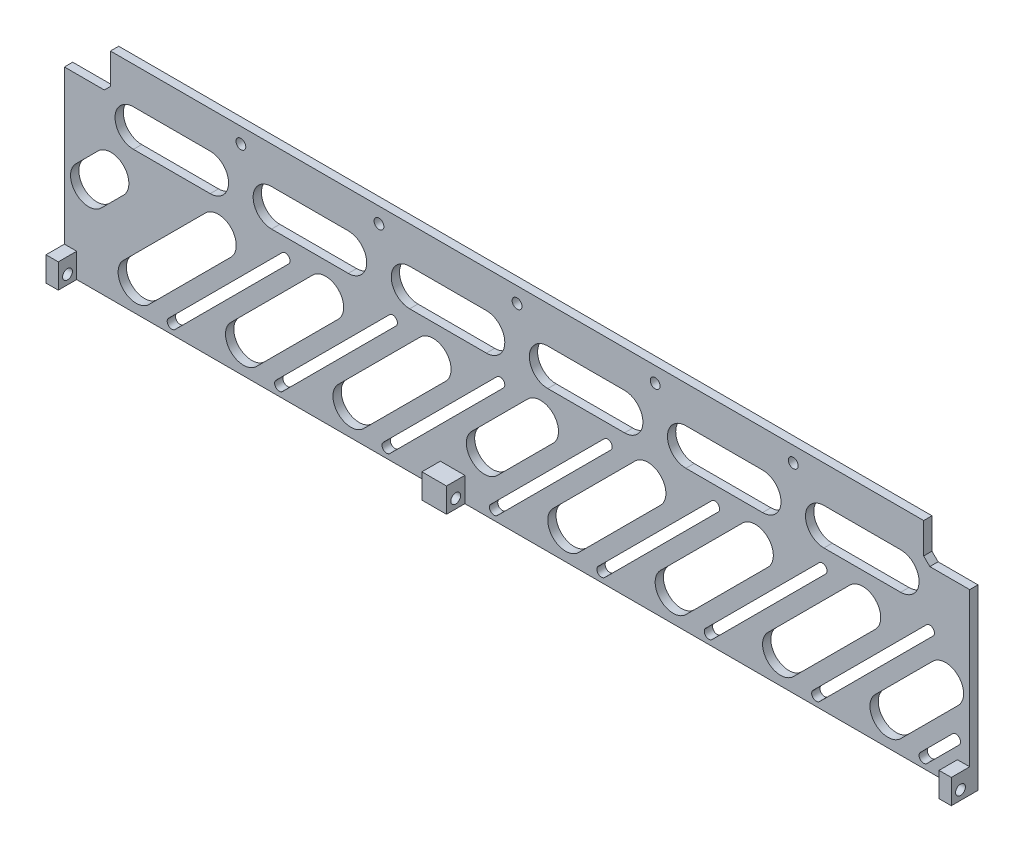
SolidWorks part; units mm, degrees
ref_plane "前视基准面" through (0, 0, 0) normal (0, 0, 1) x (1, 0, 0)
ref_plane "上视基准面" through (0, 0, 0) normal (0, 1, 0) x (1, 0, 0)
ref_plane "右视基准面" through (0, 0, 0) normal (1, 0, 0) x (0, 0, -1)
sketch "草图1" plane through (0, 0, 0) normal (0, 0, 1) x (1, 0, 0)
  line L1 (-147.5, 35) -> (147.5, 35)
  line L2 (-147.5, 35) -> (-147.5, -35)
  line L3 (-147.5, -35) -> (147.5, -35)
  line L4 (147.5, 35) -> (147.5, -35)
  line L5 (-147.5, 35) -> (147.5, -35) construction
  line L6 (-147.5, -35) -> (147.5, 35) construction
  point P0 (0, 0)
  dimension "D1" = 295
  dimension "D2" = 70
extrude "凸台-拉伸1" add sketch "草图1" along normal blind 2.7
sketch "草图11" plane through (0, 0, 2.7) normal (0, 0, 1) x (1, 0, 0)
  line L0 (-147.5, 35) -> (-147.5, 23)
  line L1 (-147.5, 35) -> (-147.5, -35) construction
  line L2 (-147.5, 23) -> (-134.5, 23)
  line L3 (-134.5, 23) -> (-132.5, 25)
  line L4 (-132.5, 25) -> (-132.5, 35)
  line L5 (147.5, 35) -> (-147.5, 35) construction
  line L6 (-132.5, 35) -> (-147.5, 35)
  line L13 (0, 35) -> (0, -35) construction
  line L14 (-147.5, -35) -> (147.5, -35) construction
  line L15 (132.5, 35) -> (147.5, 35)
  line L16 (132.5, 25) -> (132.5, 35)
  line L17 (134.5, 23) -> (132.5, 25)
  line L18 (147.5, 23) -> (134.5, 23)
  line L19 (147.5, 35) -> (147.5, 23)
  dimension "D1" = 15
  dimension "D2" = 12
  dimension "D3" = 135
  dimension "D4" = 10
extrude "切除-拉伸5" cut sketch "草图11" against normal blind 10
sketch "草图2" plane through (0, 0, 2.7) normal (0, 0, 1) x (1, 0, 0)
  line L1 (0, -32) -> (0, 35) construction
  line L2 (132.5, 35) -> (-132.5, 35) construction
  line L3 (-147.5, 23) -> (-147.5, -35) construction
  line L4 (-112.5, -32) -> (-75.5, 5) construction
  line L5 (-113.5607, -30.9393) -> (-76.5607, 6.0607)
  line L6 (-111.4393, -33.0607) -> (-74.4393, 3.9393)
  line L7 (-147.5, -35) -> (147.5, -35) construction
  arc A1 (-113.5607, -30.9393) -> (-111.4393, -33.0607) centre (-112.5, -32) ccw
  arc A2 (-74.4393, 3.9393) -> (-76.5607, 6.0607) centre (-75.5, 5) ccw
  point P4 (-94, -13.5)
  dimension "D2" = 3
  dimension "D3" = 45
  dimension "D4" = 3
  dimension "D5" = 40
  dimension "D10" = 35
extrude "切除-拉伸1" cut sketch "草图2" against normal through all
pattern_linear "阵列(线性)1" count 7 spacing 35 along (1, 0, 0) of "切除-拉伸1"
sketch "草图10" plane through (0, 0, 2.7) normal (0, 0, 1) x (1, 0, 0)
  line L0 (132.5, -32) -> (143, -21.5) construction
  line L3 (131.4393, -30.9393) -> (141.9393, -20.4393)
  line L9 (133.5607, -33.0607) -> (144.0607, -22.5607)
  line L13 (62.5, -32) -> (132.5, -32) construction
  line L14 (147.5, -35) -> (147.5, 23) construction
  line L15 (63.5607, -33.0607) -> (100.5607, 3.9393) construction
  line L16 (144.5, -8.0249) -> (144.5, -29.8766) construction
  arc A4 (131.4393, -30.9393) -> (133.5607, -33.0607) centre (132.5, -32) ccw
  arc A5 (144.0607, -22.5607) -> (141.9393, -20.4393) centre (143, -21.5) ccw
  point P2 (137.75, -26.75)
  dimension "D1" = 15
  dimension "D2" = 70
  dimension "D3" = 3
  dimension "D4" = 3
extrude "切除-拉伸4" cut sketch "草图10" against normal through all
sketch "草图5" plane through (0, 0, 2.7) normal (0, 0, 1) x (1, 0, 0)
  line L0 (-147.5, -35) -> (147.5, -35) construction
  line L1 (-147.5, -35) -> (-143.5, -35)
  line L2 (-147.5, -35) -> (-147.5, -27)
  line L3 (-147.5, -27) -> (-143.5, -27)
  line L4 (-143.5, -35) -> (-143.5, -27)
  line L5 (147.5, -35) -> (143.5, -35)
  line L6 (147.5, -35) -> (147.5, -27)
  line L7 (147.5, -27) -> (143.5, -27)
  line L8 (143.5, -35) -> (143.5, -27)
  line L9 (-25, -35) -> (-17, -35)
  line L10 (-25, -35) -> (-25, -27)
  line L11 (-25, -27) -> (-17, -27)
  line L12 (-17, -35) -> (-17, -27)
  line L13 (-21, -32) -> (-7.5, -32) construction
  line L14 (-21, -32) -> (-21, -27) construction
  dimension "D1" = 8
  dimension "D2" = 8
  dimension "4" = 4
  dimension "D3" = 13.5
extrude "凸台-拉伸3" add sketch "草图5" along normal blind 6
sketch "草图7" plane through (-143.5, 0, 0) normal (1, 0, 0) x (0, 0, -1)
  line L0 (-8.7, -35) -> (-2.7, -35) construction
  line L1 (-5.7, -32) -> (-5.7, -35) construction
  circle A0 centre (-5.7, -32) radius 1.6
  dimension "D2" = 3.2
  dimension "D1" = 3
extrude "切除-拉伸3" cut sketch "草图7" against normal through all both and the other way through all
sketch "草图12" plane through (0, 0, 2.7) normal (0, 0, 1) x (1, 0, 0)
  line L0 (-89.1256, -26.1256) -> (-62.3744, 0.6256) construction
  line L1 (-93.2794, -21.9718) -> (-66.5282, 4.7794)
  line L2 (-84.9718, -30.2794) -> (-58.2206, -3.5282)
  line L3 (-76.5607, 6.0607) -> (-113.5607, -30.9393) construction
  line L4 (-111.4393, -33.0607) -> (-74.4393, 3.9393) construction
  line L5 (-41.5607, 6.0607) -> (-78.5607, -30.9393) construction
  line L6 (-143.5, -35) -> (-25, -35) construction
  line L7 (-88.1053, 6.5) -> (-19.4368, 6.5) construction
  line L8 (-59.1196, -32) -> (-128.8233, -32) construction
  arc A0 (-93.2794, -21.9718) -> (-84.9718, -30.2794) centre (-89.1256, -26.1256) ccw
  arc A1 (-58.2206, -3.5282) -> (-66.5282, 4.7794) centre (-62.3744, 0.6256) ccw
  arc A3 (-74.4393, 3.9393) -> (-76.5607, 6.0607) centre (-75.5, 5) ccw construction
  point P2 (-75.75, -12.75)
  dimension "D3" = 3
  dimension "D1" = 5
  dimension "D2" = 5
extrude "切除-拉伸6" cut sketch "草图12" against normal through all
pattern_linear "阵列(线性)2" count 7 spacing 35 along (1, 0, 0) of "切除-拉伸6"
pattern_linear "阵列(线性)3" count 3 spacing 35 along (-1, 0, 0) of "切除-拉伸6"
sketch "草图13" plane through (0, 0, 2.7) normal (0, 0, 1) x (1, 0, 0)
  line L0 (-35, 17) -> (-10, 17) construction
  line L1 (-35, 23) -> (-10, 23)
  line L2 (-35, 11) -> (-10, 11)
  line L3 (132.5, 35) -> (-132.5, 35) construction
  line L5 (0, 35) -> (0, -79.5814) construction
  arc A0 (-35, 23) -> (-35, 11) centre (-35, 17) ccw
  arc A1 (-10, 11) -> (-10, 23) centre (-10, 17) ccw
  point P2 (-22.5, 17)
  dimension "D1" = 18
  dimension "D2" = 25
  dimension "D3" = 12
  dimension "D4" = 22.5
extrude "切除-拉伸7" cut sketch "草图13" against normal through all
pattern_linear "阵列(线性)4" count 4 spacing 45 along (1, 0, 0) of "切除-拉伸7"
pattern_linear "阵列(线性)5" count 3 spacing 45 along (-1, 0, 0) of "切除-拉伸7"
sketch "草图14" plane through (0, 0, 2.7) normal (0, 0, 1) x (1, 0, 0)
  line L0 (-136.5282, 4.7794) -> (-147.5, -6.1924) construction
  line L3 (3.4718, 4.7794) -> (-23.2794, -21.9718) construction
  line L6 (143.4718, 4.7794) -> (116.7206, -21.9718) construction
  line L7 (145.5, 14.2028) -> (145.5, -16.5331) construction
  line L8 (147.5, -27) -> (147.5, -7.8076) construction
  line L9 (-145.5, 6.8282) -> (-145.5, -26.8886) construction
  line L10 (-147.5, 23) -> (-147.5, -6.1924) construction
  line L11 (-14.9718, -30.2794) -> (11.7794, -3.5282) construction
  line L12 (-143.7794, -2.4718) -> (-147.5, -6.1924)
  line L13 (-147.5, -6.1924) -> (-147.5, -22.8076)
  line L14 (-147.5, -22.8076) -> (-135.4718, -10.7794)
  line L15 (143.4718, 4.7794) -> (135.4718, -3.2206)
  line L16 (125.0282, -30.2794) -> (147.5, -7.8076) construction
  line L17 (143.7794, -11.5282) -> (147.5, -7.8076)
  line L18 (147.5, 6.4987) -> (147.5, -7.8076)
  line L21 (-14.7942, -13.4865) -> (-23.2794, -21.9718)
  line L25 (-10.6403, -17.6403) -> (-19.1256, -26.1256) construction
  line L26 (-6.4865, -21.7942) -> (-14.9718, -30.2794)
  arc A1 (-143.7794, -2.4718) -> (-135.4718, -10.7794) centre (-139.6256, -6.6256) ccw
  arc A3 (143.7794, -11.5282) -> (135.4718, -3.2206) centre (139.6256, -7.3744) ccw
  arc A4 (147.5, 6.4987) -> (143.4718, 4.7794) centre (147.6256, 0.6256) ccw construction
  arc A5 (147.5, 6.4987) -> (143.4718, 4.7794) centre (147.6256, 0.6256) ccw
  arc A7 (-23.2794, -21.9718) -> (-14.9718, -30.2794) centre (-19.1256, -26.1256) ccw
  arc A8 (-23.2794, -21.9718) -> (-24.9346, -27) centre (-19.1256, -26.1256) ccw construction
  arc A9 (-14.7942, -13.4865) -> (-6.4865, -21.7942) centre (-10.6403, -17.6403) ccw
  point P3 (-136, -3)
  point P8 (129.5, -17.5)
  dimension "D1" = 2
  dimension "D2" = 2
  dimension "D3" = 12
extrude "凸台-拉伸4" add sketch "草图14" against normal up to surface (2.7 mm away) up to face at (-67.5, 17, 0)
sketch "草图15" plane through (0, 0, 2.7) normal (0, 0, 1) x (1, 0, 0)
  line L0 (-100, 17) -> (-80, 17) construction
  line L1 (132.5, 35) -> (-132.5, 35) construction
  line L2 (-55, 17) -> (-35, 17) construction
  line L3 (55, 17) -> (35, 17) construction
  line L4 (100, 17) -> (80, 17) construction
  line L5 (-10, 17) -> (10, 17) construction
  circle A0 centre (-90, 30) radius 1.6
  circle A1 centre (-45, 30) radius 1.6
  circle A2 centre (45, 30) radius 1.6
  circle A3 centre (90, 30) radius 1.6
  circle A4 centre (0, 30) radius 1.6
  point P8 (-90, 17)
  point P20 (-45, 17)
  point P29 (90, 17)
  point P31 (45, 17)
  point P37 (0, 17)
  dimension "D1" = 3.2
  dimension "D2" = 5
extrude "切除-拉伸8" cut sketch "草图15" against normal blind 10
